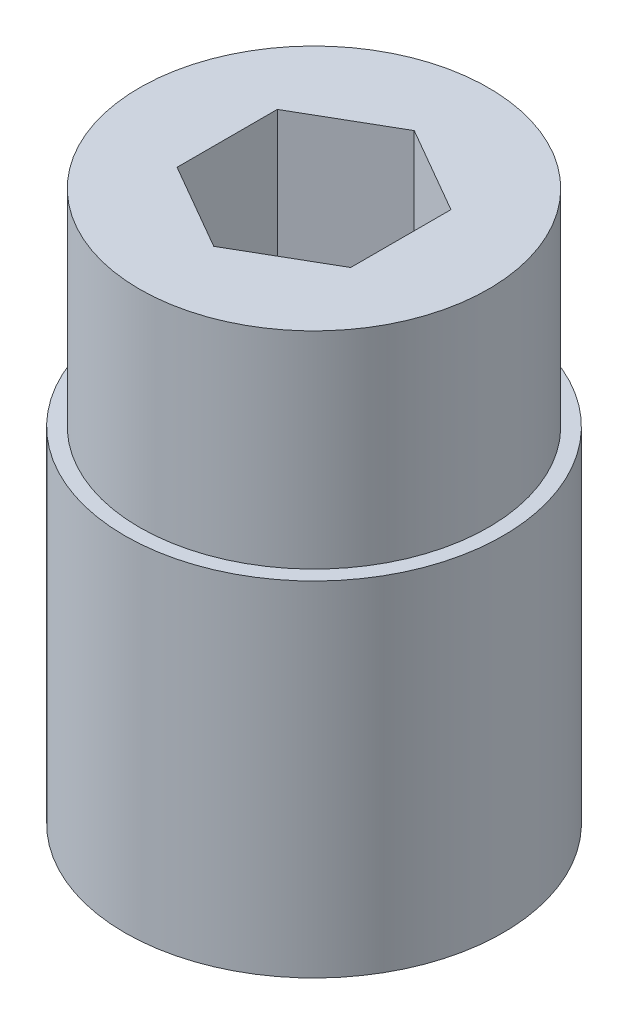
SolidWorks part; units mm, degrees
ref_plane "Front Plane" through (0, 0, 0) normal (0, 0, 1) x (1, 0, 0)
ref_plane "Top Plane" through (0, 0, 0) normal (0, 1, 0) x (1, 0, 0)
ref_plane "Right Plane" through (0, 0, 0) normal (1, 0, 0) x (0, 0, -1)
sketch "Sketch1" plane through (0, 0, 0) normal (0, 1, 0) x (1, 0, 0)
  circle A0 centre (0, 0) radius 7
  dimension "D1" = 14
extrude "Boss-Extrude1" add sketch "Sketch1" along normal blind 10
sketch "Sketch2" plane through (0, 10, 0) normal (0, 1, 0) x (1, 0, 0)
  circle A0 centre (0, 0) radius 5.075
  dimension "D1" = 10.15
extrude "Boss-Extrude2" add sketch "Sketch2" along normal blind 6
sketch "Sketch3" plane through (0, 16, 0) normal (0, 1, 0) x (1, 0, 0)
  line L1 (3.5, -1.4434) -> (3.5, 1.4434)
  line L2 (3.5, 1.4434) -> (1, 2.8868)
  line L3 (1, 2.8868) -> (-1.5, 1.4434)
  line L4 (-1.5, 1.4434) -> (-1.5, -1.4434)
  line L5 (-1.5, -1.4434) -> (1, -2.8868)
  line L6 (1, -2.8868) -> (3.5, -1.4434)
  circle A0 centre (1, 0) radius 2.5 construction
  dimension "D1" = 5
  dimension "D2" = 1
extrude "Cut-Extrude1" [suppressed] cut sketch "Sketch3" against normal through all
sketch "Sketch4" plane through (0, 16, 0) normal (0, 1, 0) x (1, 0, 0)
  line L1 (2.525, 1.4578) -> (0, 2.9156)
  line L2 (0, 2.9156) -> (-2.525, 1.4578)
  line L3 (-2.525, 1.4578) -> (-2.525, -1.4578)
  line L4 (-2.525, -1.4578) -> (0, -2.9156)
  line L5 (0, -2.9156) -> (2.525, -1.4578)
  line L6 (2.525, -1.4578) -> (2.525, 1.4578)
  circle A0 centre (0, 0) radius 2.525 construction
  dimension "D1" = 5.05
extrude "Cut-Extrude2" cut sketch "Sketch4" against normal through all
sketch "Sketch5" plane through (0, 10, 0) normal (0, 1, 0) x (1, 0, 0)
  circle A0 centre (0, 0) radius 5.5
  dimension "D1" = 11
extrude "Cut-Extrude3" cut sketch "Sketch5" against normal through all flip side to cut
equation "\"R_ROLL\"= 5mm"
equation "\"D_SUN\"= 80mm"
equation "\"NUM_ROLL\"= 16"
equation "\"RHO\"= 1mm"
equation "\"D_SHAFT\"= 15mm"
equation "\"D_OUTPUT\"= 40mm"
equation "\"NUM_OUT\"= 6"
equation "\"R_OUT_ROLL\"= 5mm"
